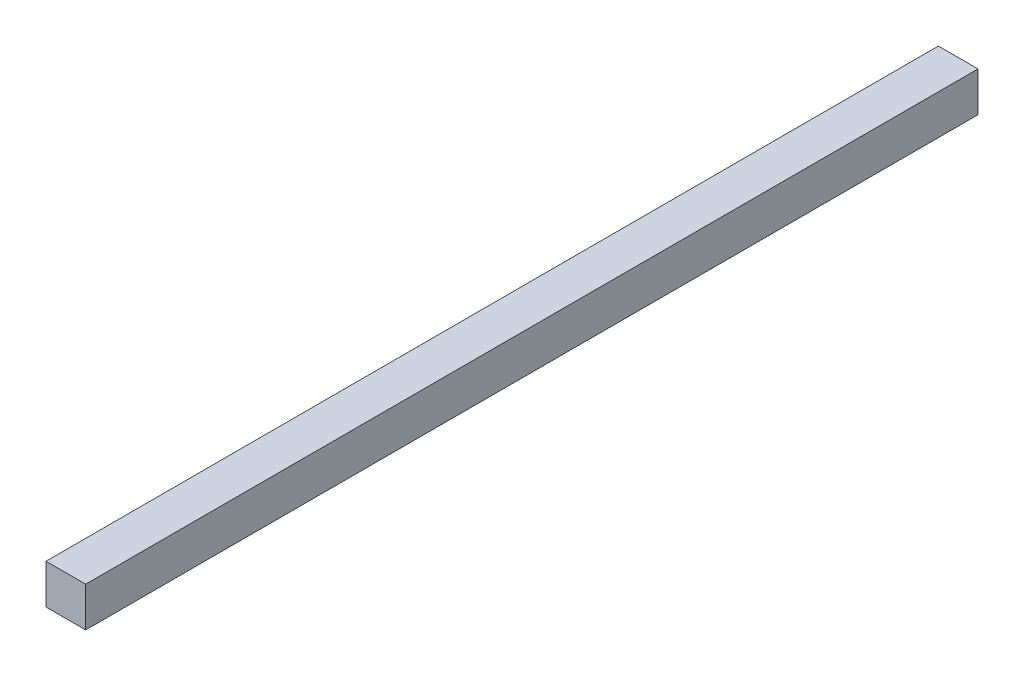
SolidWorks part; units mm, degrees
material "6061-T6 (SS)"
ref_plane "Front Plane" through (0, 0, 0) normal (0, 0, 1) x (1, 0, 0)
ref_plane "Top Plane" through (0, 0, 0) normal (0, 1, 0) x (1, 0, 0)
ref_plane "Right Plane" through (0, 0, 0) normal (1, 0, 0) x (0, 0, -1)
sketch "Sketch1" plane through (0, 0, 0) normal (0, 0, 1) x (1, 0, 0)
  line L1 (0, 0) -> (2.54, 0)
  line L2 (0, 0) -> (0, 2.54)
  line L3 (0, 2.54) -> (2.54, 2.54)
  line L4 (2.54, 0) -> (2.54, 2.54)
  dimension "D1" = 2.54
  dimension "D2" = 2.54
extrude "Boss-Extrude1" add sketch "Sketch1" along normal blind 57.15
equation "\"b\"= .1'base of beam(in)"
equation "\"h\" = .1'height of beam(in)"
equation "\"Area\"= \"b\" * \"h\"'cross sectional area(in^2)"
equation "\"F\"= 400'load in pounds"
equation "\"del\"= .009'max deflection(in)"
equation "\"E\" = 10000000'youngs modules(psi)"
equation "\"L\"= \"del\" * \"Area\" * \"E\" / \"F\"'desinged length(in)"
equation "\"D1@Sketch1\"=\"h\""
equation "\"D2@Sketch1\"=\"b\""
equation "\"D1@Boss-Extrude1\"=\"L\""
